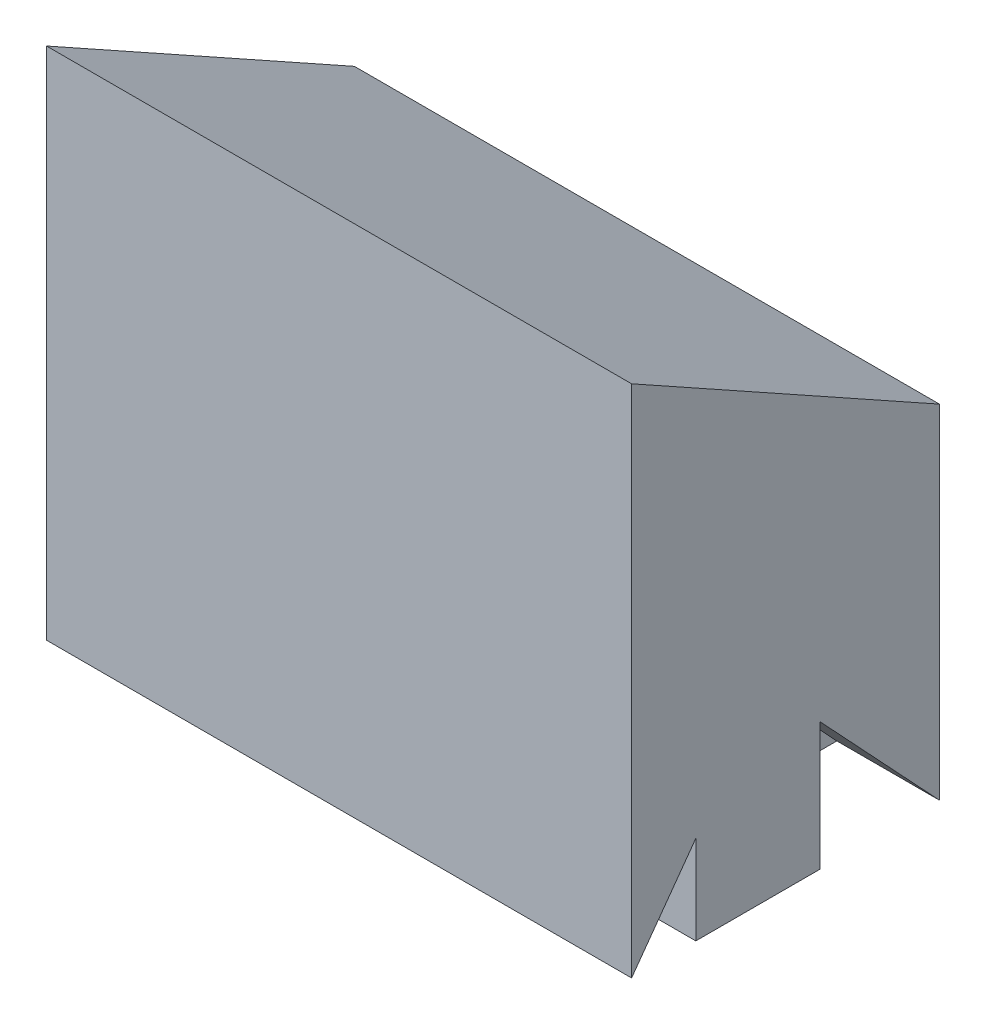
SolidWorks part; units mm, degrees
ref_plane "前基準面" through (0, 0, 0) normal (0, 0, 1) x (1, 0, 0)
ref_plane "上基準面" through (0, 0, 0) normal (0, 1, 0) x (1, 0, 0)
ref_plane "右基準面" through (0, 0, 0) normal (1, 0, 0) x (0, 0, -1)
sketch "草圖1" plane through (0, 0, 0) normal (0, 0, 1) x (1, 0, 0)
  line L0 (13.8495, 0) -> (70.8578, 0)
  line L1 (70.8578, 0) -> (70.8578, 72.5112)
  line L2 (70.8578, 72.5112) -> (13.8495, 72.5112)
  line L3 (13.8495, 72.5112) -> (13.8495, 0)
  line L4 (13.8495, 0) -> (-50.7902, 0.8797)
  line L5 (13.8495, 50.1421) -> (70.8578, 50.1421)
  line L6 (70.8578, 50.1421) -> (71.1091, 50.1421)
extrude "填料-伸長2" add sketch "草圖1" along normal blind 30 contours L5 L3 L0 L1
sketch "草圖2" plane through (13.8495, 0, 0) normal (-1, 0, 0) x (0, 0, 1)
  line L0 (30, 50.1421) -> (0, 33.4265)
  line L1 (0, 50.1421) -> (0, 0) construction
  line L2 (0, 50.1421) -> (0, 33.4265)
  line L3 (0, 50.1421) -> (30, 50.1421)
extrude "除料-伸長1" cut sketch "草圖2" against normal through all
sketch "草圖3" plane through (70.8578, 0, 0) normal (1, 0, 0) x (0, 0, -1)
  line L0 (-11.6438, 0) -> (-11.6438, 12.4504)
  line L1 (-30, 0) -> (0, 0) construction
  line L2 (-11.6438, 12.4504) -> (0, 12.4504)
  line L3 (0, 0) -> (0, 33.4265) construction
  line L4 (-11.6438, 12.4504) -> (0, 0)
  line M5 (-30, 0) -> (0, 0)
extrude "除料-伸長2" cut sketch "草圖3" against normal blind 10 contours L4 L0 M5
sketch "草圖5" plane through (0, 0, 30) normal (0, 0, 1) x (1, 0, 0)
  line L0 (13.8495, 19.5823) -> (43.0529, 19.5823)
  line L1 (13.8495, 50.1421) -> (13.8495, 0) construction
  line L2 (43.0529, 19.5823) -> (43.0529, 0)
  line L3 (13.8495, 0) -> (70.8578, 0) construction
  line L4 (43.0529, 0) -> (43.0529, 15.0375)
  line L5 (43.0529, 15.0375) -> (70.8578, 15.0375)
  line L6 (70.8578, 0) -> (70.8578, 50.1421) construction
  line L7 (70.8578, 15.0375) -> (70.8578, 0)
  line L8 (70.8578, 0) -> (43.0529, 0)
  line L9 (43.0529, 0) -> (43.1927, 0.0046)
  line L10 (13.8495, 0) -> (13.8495, 19.5823)
sketch "草圖6" plane through (13.8495, 0, 0) normal (-1, 0, 0) x (0, 0, 1)
  line L0 (30, 0) -> (20.2258, 16.6021)
  line L1 (20.2258, 16.6021) -> (20.2258, 0)
  line L2 (30, 0) -> (0, 0) construction
  line L3 (20.2258, 0) -> (30, 0)
extrude "除料-伸長3" cut sketch "草圖6" against normal blind 28
sketch "草圖7" plane through (70.8578, 0, 0) normal (1, 0, 0) x (0, 0, -1)
  line L0 (-30, 0) -> (-23.7428, 8.6563)
  line L1 (-23.7428, 8.6563) -> (-23.7428, 0)
  line L2 (-30, 0) -> (-11.6438, 0) construction
  line L3 (-23.7428, 0) -> (-30, 0)
extrude "除料-伸長4" cut sketch "草圖7" against normal through all
